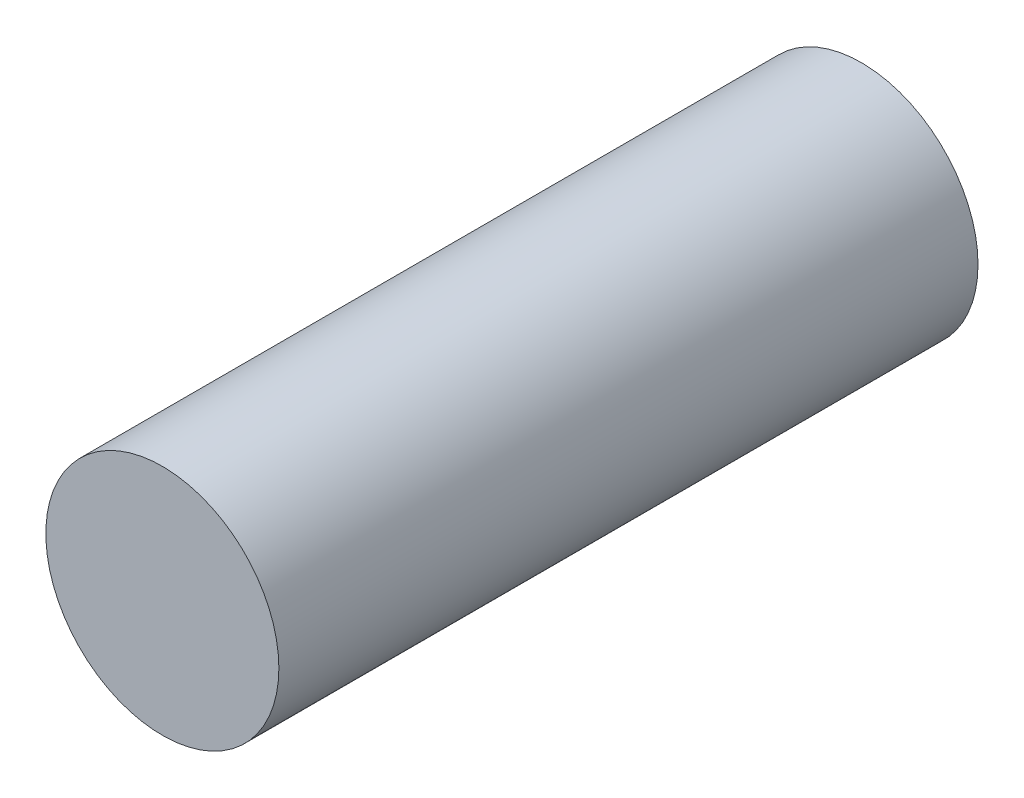
SolidWorks part; units mm, degrees
material "AISI Type A2 Tool Steel"
ref_plane "Front Plane" through (0, 0, 0) normal (1, 0, 0) x (0, 1, 0)
ref_plane "Top Plane" through (0, 0, 0) normal (0, 0, 1) x (0, 1, 0)
ref_plane "Right Plane" through (0, 0, 0) normal (0, 1, 0) x (-1, 0, 0)
sketch "Sketch1" plane through (0, 0, 0) normal (0, 0, 1) x (0, 1, 0)
  circle A0 centre (0, 0) radius 6.65
  dimension "D1" = 13.3
extrude "Boss-Extrude1" add sketch "Sketch1" along normal blind 39.9
